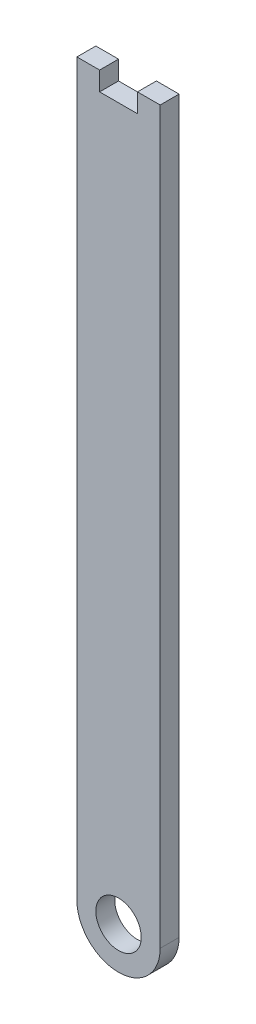
SolidWorks part; units mm, degrees
ref_plane "Front Plane" through (0, 0, 0) normal (1, 0, 0) x (0, 1, 0)
ref_plane "Top Plane" through (0, 0, 0) normal (0, 0, 1) x (0, 1, 0)
ref_plane "Right Plane" through (0, 0, 0) normal (0, 1, 0) x (-1, 0, 0)
sketch "Sketch1" plane through (0, 0, 0) normal (0, 0, 1) x (0, 1, 0)
  line L0 (0, 11) -> (193, 11)
  line L1 (0, -11) -> (193, -11)
  line L14 (193, 11) -> (193, -11) construction
  line L15 (193, 0) -> (188, 0) construction
  line L16 (188, -5) -> (188, 5)
  line L17 (188, 5) -> (193, 5)
  line L18 (188, -5) -> (193, -5)
  line L19 (193, -5) -> (193, -11)
  line L20 (193, 5) -> (193, 11)
  circle A0 centre (0, 0) radius 6
  arc A1 (0, 11) -> (0, -11) centre (0, 0) ccw
  arc A2 (0, -11) -> (0, 11) centre (0, 0) ccw construction
  circle A3 centre (0, 0) radius 11 construction
  point P12 (188, 0)
  dimension "D2" = 12
  dimension "D3" = 193
  dimension "D4" = 10
  dimension "D5" = 5
  dimension "D1" = 5
extrude "Boss-Extrude1" add sketch "Sketch1" along normal mid plane 5
